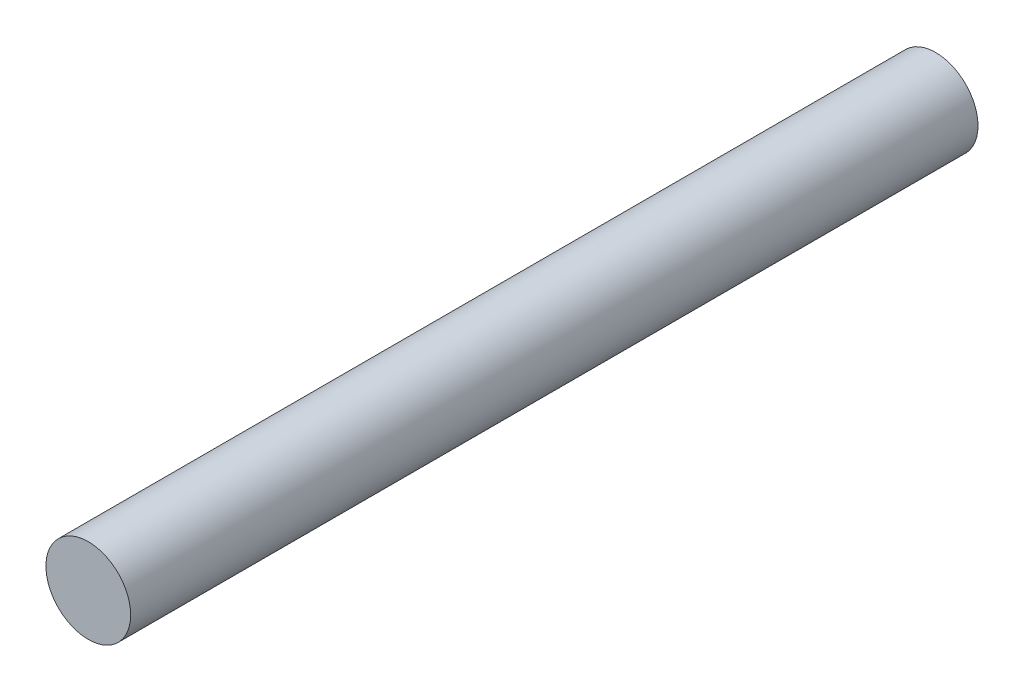
SolidWorks part; units mm, degrees
ref_plane "前视基准面" through (0, 0, 0) normal (0, 0, 1) x (1, 0, 0)
ref_plane "上视基准面" through (0, 0, 0) normal (0, 1, 0) x (1, 0, 0)
ref_plane "右视基准面" through (0, 0, 0) normal (1, 0, 0) x (0, 0, -1)
other "Configuration Table"
sketch "草图1" plane through (0, 0, 0) normal (0, 0, 1) x (1, 0, 0)
  circle A0 centre (0, 0) radius 1
  dimension "D1" = 2
extrude "凸台-拉伸1" add sketch "草图1" along normal mid plane 20
